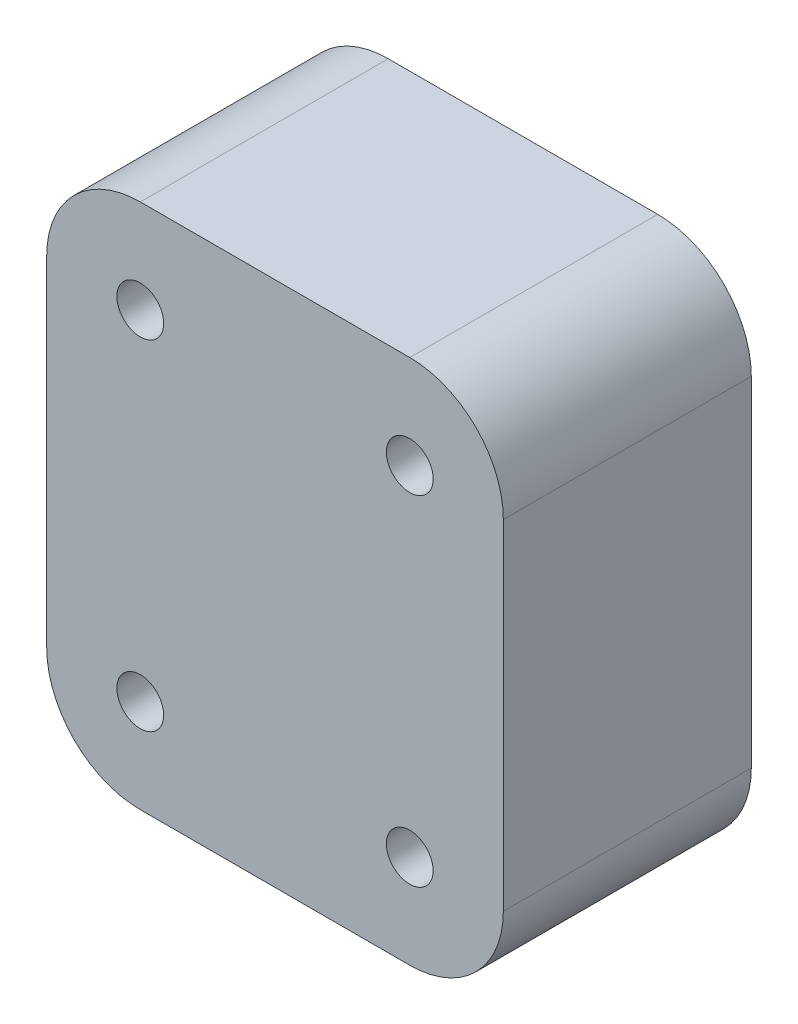
SolidWorks part; units mm, degrees
ref_plane "Front Plane" through (0, 0, 0) normal (0, 0, 1) x (1, 0, 0)
ref_plane "Top Plane" through (0, 0, 0) normal (0, 1, 0) x (1, 0, 0)
ref_plane "Right Plane" through (0, 0, 0) normal (1, 0, 0) x (0, 0, -1)
sketch "Sketch1" plane through (0, 0, 0) normal (0, 0, 1) x (1, 0, 0)
  line L0 (-40.1938, 28.125) -> (-40.1938, -28.125)
  line L1 (-30.1938, 18.125) -> (-1.3938, 18.125) construction
  line L2 (-30.1938, 18.125) -> (-30.1938, -18.125) construction
  line L3 (-30.1938, -18.125) -> (-1.3938, -18.125) construction
  line L4 (-1.3938, 18.125) -> (-1.3938, -18.125) construction
  line L5 (-40.1938, -28.125) -> (8.6062, -28.125)
  line L6 (8.6062, 28.125) -> (8.6062, -28.125)
  line L7 (-40.1938, 28.125) -> (8.6062, 28.125)
  circle A4 centre (-1.3938, -18.125) radius 2.5
  circle A5 centre (-30.1938, -18.125) radius 2.5
  circle A6 centre (-1.3938, 18.125) radius 2.5
  circle A7 centre (-30.1938, 18.125) radius 2.5
  dimension "D1" = 10
extrude "Boss-Extrude1" add sketch "Sketch1" along normal blind 26.5
fillet "Fillet1" radius 10 4 edges at (-40.1938, -28.125, 13.25) (-40.1938, 28.125, 13.25) (8.6062, -28.125, 13.25) (8.6062, 28.125, 13.25)
